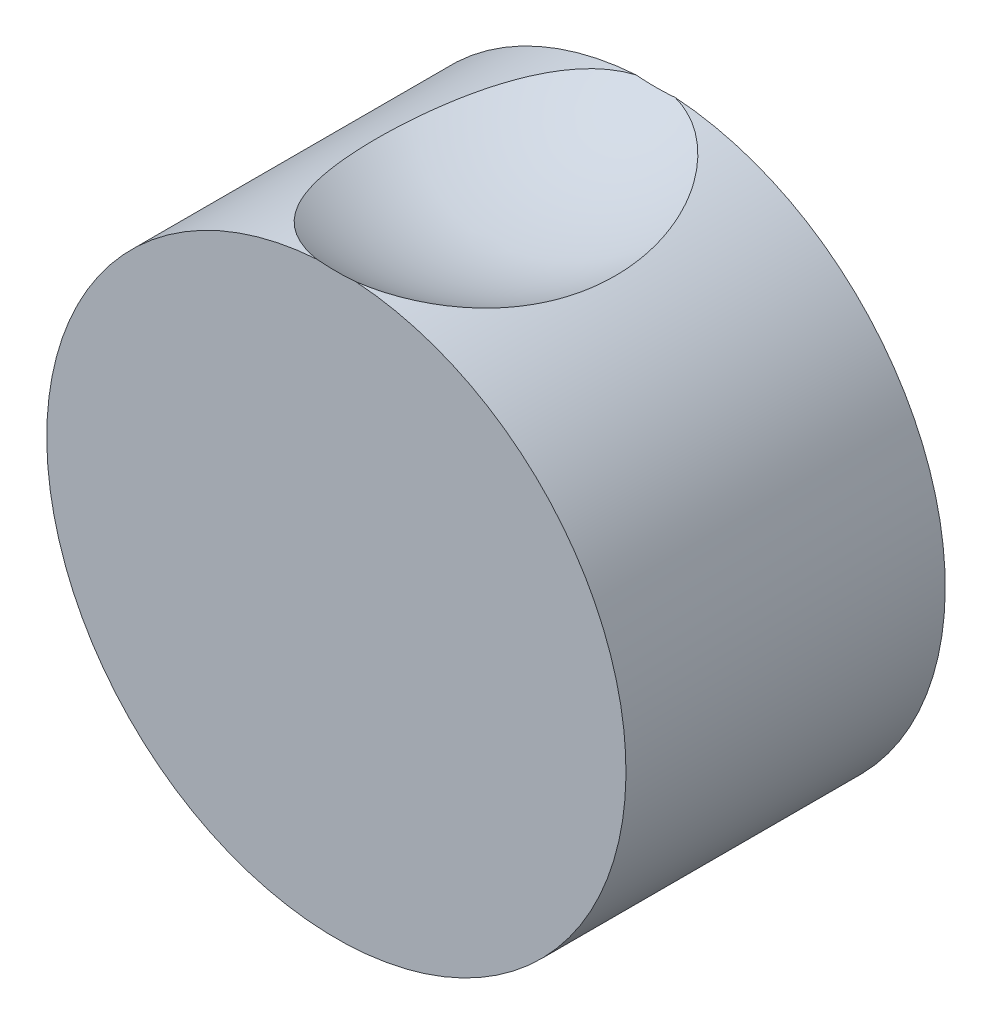
SolidWorks part; units mm, degrees
ref_plane "Front Plane" through (0, 0, 0) normal (0, 0, 1) x (1, 0, 0)
ref_plane "Top Plane" through (0, 0, 0) normal (0, 1, 0) x (1, 0, 0)
ref_plane "Right Plane" through (0, 0, 0) normal (1, 0, 0) x (0, 0, -1)
sketch "Sketch1" plane through (0, 0, 0) normal (0, 0, 1) x (1, 0, 0)
  circle A0 centre (0, 0) radius 12.7
  dimension "D1" = 25.4
extrude "Boss-Extrude1" add sketch "Sketch1" along normal mid plane 14
sketch "Sketch3" plane through (0, 0, 0) normal (1, 0, 0) x (0, 0, -1)
  line L8 (0, 34.3805) -> (0, 10.3805)
  arc A0 (0, 10.3805) -> (0, 34.3805) centre (0, 22.3805) ccw
  dimension "D1" = 24
revolve "Cut-Revolve1" cut sketch "Sketch3" angle 360 about L8
